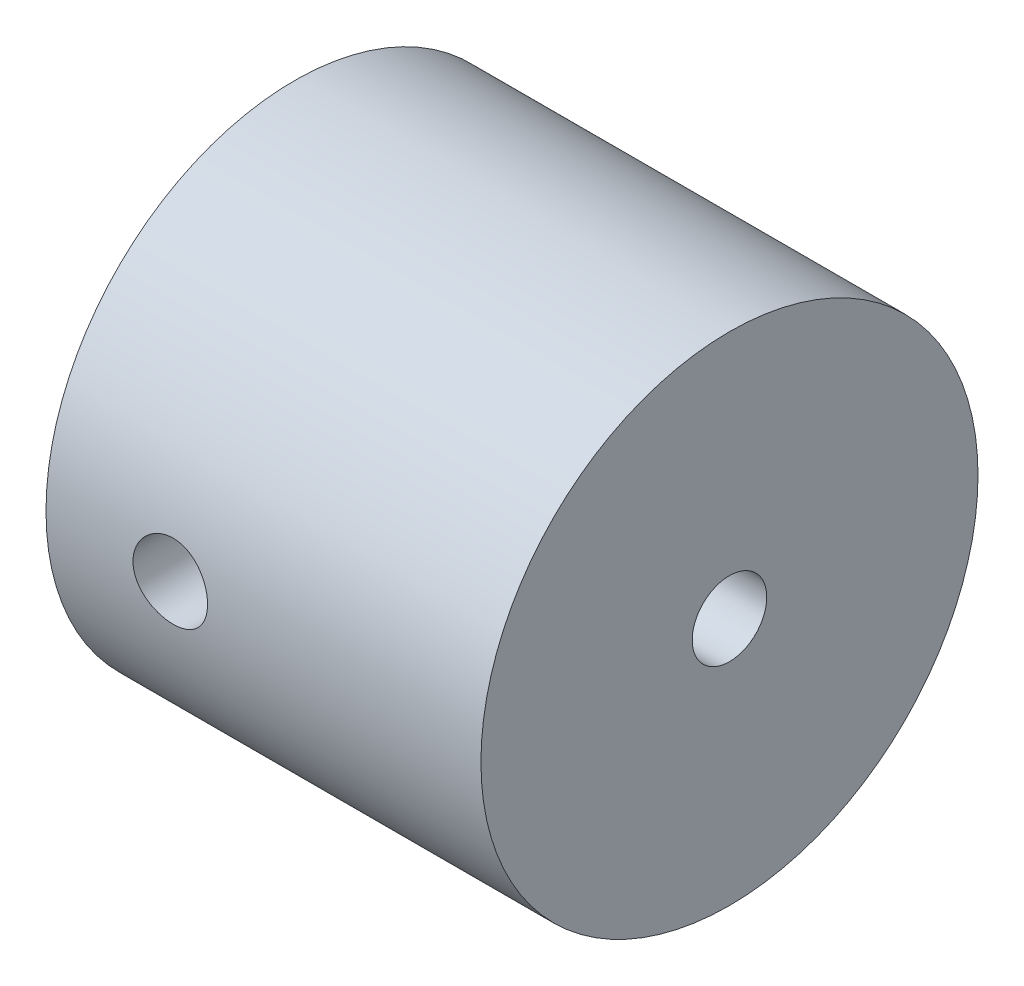
SolidWorks part; units mm, degrees
material "1060 合金"
ref_plane "前视基准面" through (0, 0, 0) normal (0, 0, 1) x (1, 0, 0)
ref_plane "上视基准面" through (0, 0, 0) normal (0, 1, 0) x (1, 0, 0)
ref_plane "右视基准面" through (0, 0, 0) normal (1, 0, 0) x (0, 0, -1)
sketch "草图1" plane through (0, 0, 0) normal (1, 0, 0) x (0, 0, -1)
  circle A0 centre (0, 0) radius 20
extrude "凸台-拉伸2" add sketch "草图1" along normal blind 10 contours A0
sketch "草图2" plane through (0, 0, 0) normal (-1, 0, 0) x (0, 0, 1)
  circle A0 centre (0, 0) radius 7
  circle A1 centre (0, 0) radius 20
extrude "凸台-拉伸3" add sketch "草图2" along normal blind 25
sketch "草图3" plane through (10, 0, 0) normal (1, 0, 0) x (0, 0, -1)
  circle A0 centre (0, 0) radius 3
extrude "切除-拉伸2" cut sketch "草图3" against normal blind 10 contours A0
sketch "草图4" plane through (0, 0, 0) normal (0, 0, 1) x (1, 0, 0)
  circle A1 centre (-15, 0) radius 3
  point P3 (0, 0)
extrude "切除-拉伸3" cut sketch "草图4" against normal mid plane 40
